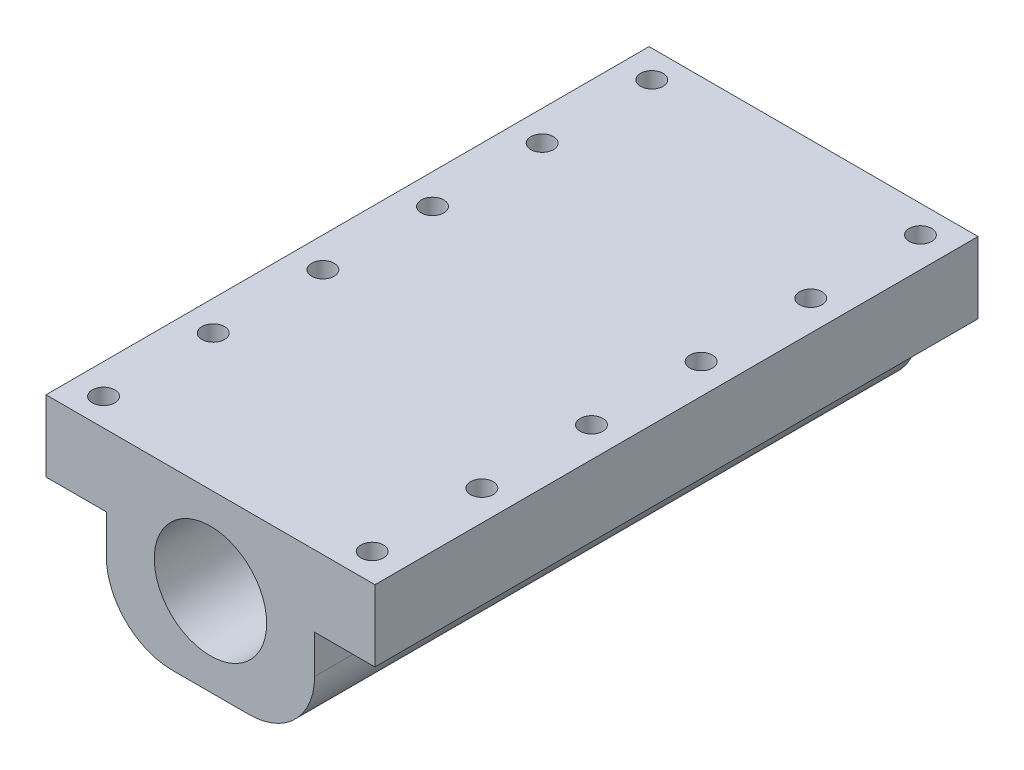
SolidWorks part; units mm, degrees
ref_plane "Alzado" through (0, 0, 0) normal (0, 0, 1) x (1, 0, 0)
ref_plane "Planta" through (0, 0, 0) normal (0, 1, 0) x (1, 0, 0)
ref_plane "Vista lateral" through (0, 0, 0) normal (1, 0, 0) x (0, 0, -1)
sketch "Croquis1" plane through (0, 0, 0) normal (0, 0, 1) x (1, 0, 0)
  line L0 (0, 0) -> (0, 16) construction
  line L1 (30, 16) -> (-30, 16)
  line L2 (-30, 16) -> (-30, 3)
  line L3 (-30, 3) -> (-19, 3)
  line L4 (-19, 3) -> (-19, -4)
  line L5 (-7, -16) -> (7, -16)
  line L7 (19, 3) -> (19, -4)
  line L8 (30, 3) -> (19, 3)
  line L9 (30, 16) -> (30, 3)
  circle A0 centre (0, 0) radius 10.25
  arc A1 (-19, -4) -> (-7, -16) centre (-7, -4) ccw
  arc A2 (19, -4) -> (7, -16) centre (7, -4) cw
  point P11 (0, 0)
  point P15 (0, -16)
  dimension "D1" = 20.5
  dimension "D8" = 12
  dimension "D2" = 13
  dimension "D3" = 30
  dimension "D4" = 19
  dimension "D5" = 16
  dimension "D6" = 16
  dimension "D7" = 11
extrude "Saliente-Extruir1" add sketch "Croquis1" along normal blind 110
sketch "Croquis2" plane through (0, 3, 0) normal (0, -1, 0) x (1, 0, 0)
  line L0 (0, 110) -> (0, 0) construction
  line L1 (-7, 110) -> (7, 110) construction
  line L2 (0, 55) -> (-30, 55) construction
  line L3 (-30, 110) -> (-30, 0) construction
  line L4 (-24.5, 110) -> (-24.5, 0) construction
  line L5 (-30, 110) -> (-19, 110) construction
  line L6 (-30, 0) -> (-19, 0) construction
  line L7 (-30, -25) -> (-30, 135) construction
  line L11 (-24.5, 125) -> (-24.5, 105) construction
  circle A0 centre (-24.5, 125) radius 2.06 construction
  circle A7 centre (-24.5, 105) radius 2.06
  circle A8 centre (-24.5, 85) radius 2.06
  circle A9 centre (-24.5, 65) radius 2.06
  circle A10 centre (-24.5, 45) radius 2.06
  circle A11 centre (-24.5, 25) radius 2.06
  circle A12 centre (-24.5, 5) radius 2.06
  circle A13 centre (24.5, 5) radius 2.06
  circle A14 centre (24.5, 25) radius 2.06
  circle A15 centre (24.5, 45) radius 2.06
  circle A16 centre (24.5, 65) radius 2.06
  circle A17 centre (24.5, 85) radius 2.06
  circle A18 centre (24.5, 105) radius 2.06
  point P18 (-30, 55)
  dimension "D3" = 4.12
  dimension "D1" = 160
  dimension "D2" = 10
  dimension "D5" = 20
  dimension "D4" = 7
extrude "Cortar-Extruir1" cut sketch "Croquis2" against normal up to next
